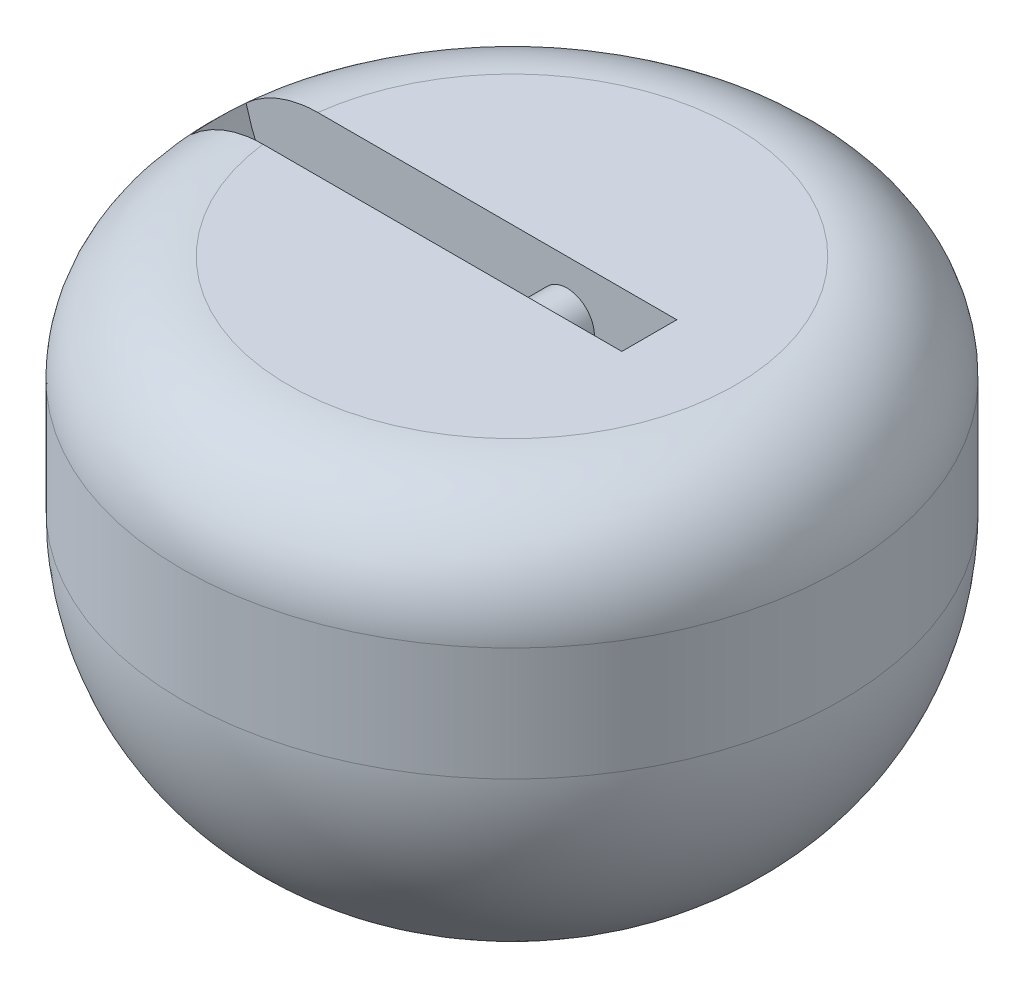
SolidWorks part; units mm, degrees
ref_plane "前视基准面" through (0, 0, 0) normal (0, 0, 1) x (1, 0, 0)
ref_plane "上视基准面" through (0, 0, 0) normal (0, 1, 0) x (1, 0, 0)
ref_plane "右视基准面" through (0, 0, 0) normal (1, 0, 0) x (0, 0, -1)
sketch "草图1" plane through (0, 0, 0) normal (0, 0, 1) x (1, 0, 0)
  line L0 (0, 0) -> (8.1309, 0)
  line L1 (12, -3.8691) -> (12, -8)
  line L2 (0, -17.6713) -> (0, 0)
  arc A0 (8.1309, 0) -> (12, -3.8691) centre (8.1309, -3.8691) cw
  arc A1 (12, -8) -> (0, -17.6713) centre (2.1027, -8) cw
  dimension "D1" = 12
  dimension "D2" = 8
revolve "旋转1" add sketch "草图1" angle 360 about L2
sketch "草图2" plane through (0, 0, 0) normal (0, 0, 1) x (1, 0, 0)
  line L1 (8.1309, 0) -> (-8.1309, 0) construction
  line L3 (0, 0) -> (5, 0)
  line L4 (0, 0) -> (-10.8745, 0)
  arc A0 (5, 0) -> (-10.8745, 0) centre (-2.9373, 1) cw
  dimension "D2" = 8
  dimension "D1" = 1
  dimension "D3" = 5
extrude "切除-拉伸1" cut sketch "草图2" against normal mid plane 2
sketch "草图3" plane through (0, 0, -1) normal (0, 0, 1) x (1, 0, 0)
  circle A0 centre (1, -2) radius 1
  circle A1 centre (-3, -5) radius 1
  dimension "D1" = 2
  dimension "D2" = 2
  dimension "D3" = 2
  dimension "D4" = 4
  dimension "D5" = 3
  dimension "D6" = 1
extrude "凸台-拉伸2" add sketch "草图3" along normal blind 2
scale "缩放比例1" scale about centroid uniform scaling yes scale factor 2
